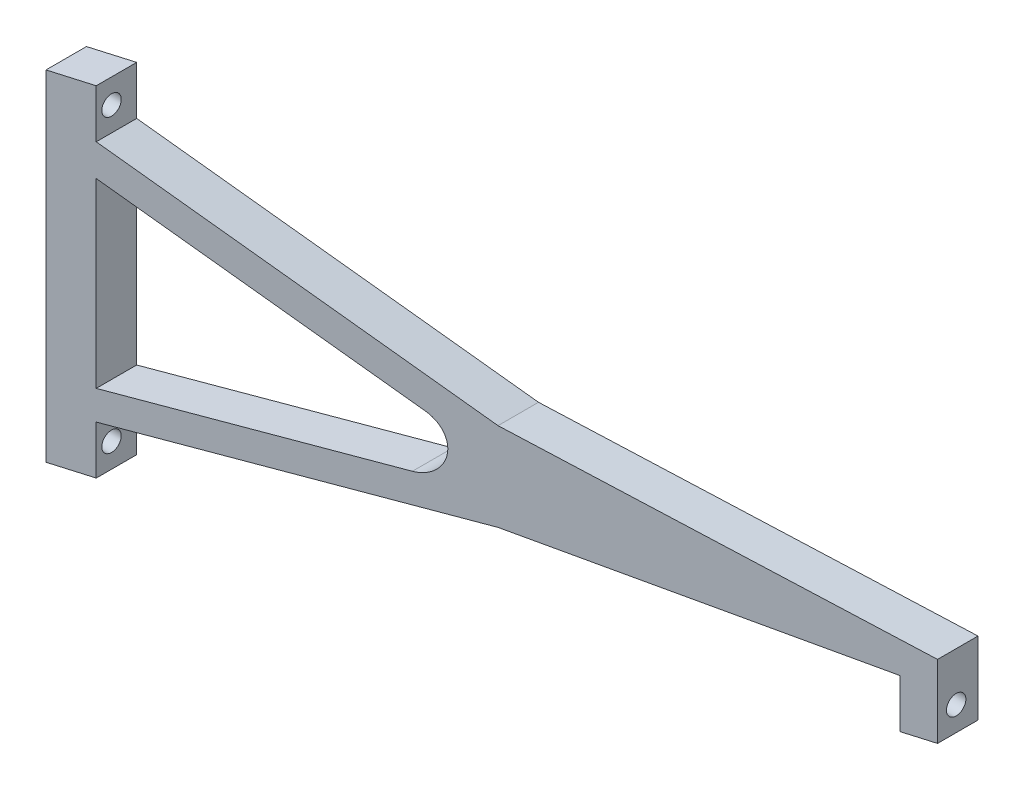
SolidWorks part; units mm, degrees
ref_plane "前视基准面" through (0, 0, 0) normal (0, 0, 1) x (1, 0, 0)
ref_plane "上视基准面" through (0, 0, 0) normal (0, 1, 0) x (1, 0, 0)
ref_plane "右视基准面" through (0, 0, 0) normal (1, 0, 0) x (0, 0, -1)
sketch "草图1" plane through (0, 0, 0) normal (0, 0, 1) x (1, 0, 0)
  line L0 (-66.744, 0) -> (65.3973, 0) construction
  line L1 (0, 48.9007) -> (0, -32.7407) construction
  line L2 (64, 10) -> (64, 0)
  line L3 (64, 0) -> (70, 0)
  line L4 (70, 0) -> (70, 15)
  line L5 (70, 15) -> (0, 31.9687)
  line L6 (0, 31.9687) -> (-64, 60)
  line L7 (-64, 60) -> (-64, 70)
  line L8 (-64, 70) -> (-72, 70)
  line L9 (-72, 70) -> (-72, 0)
  line L10 (-72, 0) -> (-64, 0)
  line L11 (-64, 0) -> (-64, 10)
  line L12 (-64, 10) -> (0, 13.8128)
  line L13 (0, 13.8128) -> (64, 10)
  line L14 (-64, 53.4497) -> (-64, 16.0106)
  line L15 (-64, 16.0106) -> (-13.6432, 19.0106)
  line L17 (-11.5928, 30.496) -> (-64, 53.4497)
  arc A0 (-13.6432, 19.0106) -> (-11.5928, 30.496) centre (-14, 25) ccw
  dimension "D14" = 6
  dimension "D1" = 15
  dimension "D2" = 10
  dimension "D3" = 70
  dimension "D4" = 10
  dimension "D5" = 10
  dimension "D6" = 6
  dimension "D7" = 6
  dimension "D8" = 50
  dimension "D9" = 142
  dimension "D10" = 6
  dimension "D11" = 8
  dimension "D12" = 70
  dimension "D13" = 25
extrude "凸台-拉伸1" add sketch "草图1" along normal mid plane 60
sketch "草图2" plane through (0, 0, 0) normal (0, 1, 0) x (1, 0, 0)
  line L0 (70, 30) -> (70, 21.6628)
  line L1 (70, -30) -> (70, 30) construction
  line L2 (70, 21.6628) -> (-72, -20)
  line L3 (-72, -30) -> (-72, 30) construction
  line L4 (-72, -20) -> (-72, -11.6628)
  line L5 (-72, -11.6628) -> (70, 30)
  dimension "D1" = 50
  dimension "D2" = 8
extrude "切除-拉伸2" cut sketch "草图2" along normal through all flip side to cut
sketch "草图3" plane through (-64, 0, 0) normal (1, 0, 0) x (0, 0, -1)
  line L0 (-17.6528, 70) -> (-9.3156, 70) construction
  line L2 (-17.6528, 0) -> (-9.3156, 0) construction
  line L4 (-20, 70) -> (-20, 0) construction
  circle A0 centre (-14.5, 65) radius 2
  circle A1 centre (-14.5, 5) radius 2
  dimension "D1" = 4
  dimension "D2" = 5
  dimension "D3" = 5.5
  dimension "D4" = 5
extrude "切除-拉伸3" cut sketch "草图3" against normal through all
sketch "草图4" plane through (70, 0, 0) normal (1, 0, 0) x (0, 0, -1)
  line L0 (21.6628, 0) -> (30, 0) construction
  line L2 (30, 0) -> (30, 15) construction
  circle A0 centre (25.5, 5) radius 2
  dimension "D1" = 4
  dimension "D2" = 5
  dimension "D3" = 4.5
extrude "切除-拉伸4" cut sketch "草图4" against normal up to next
